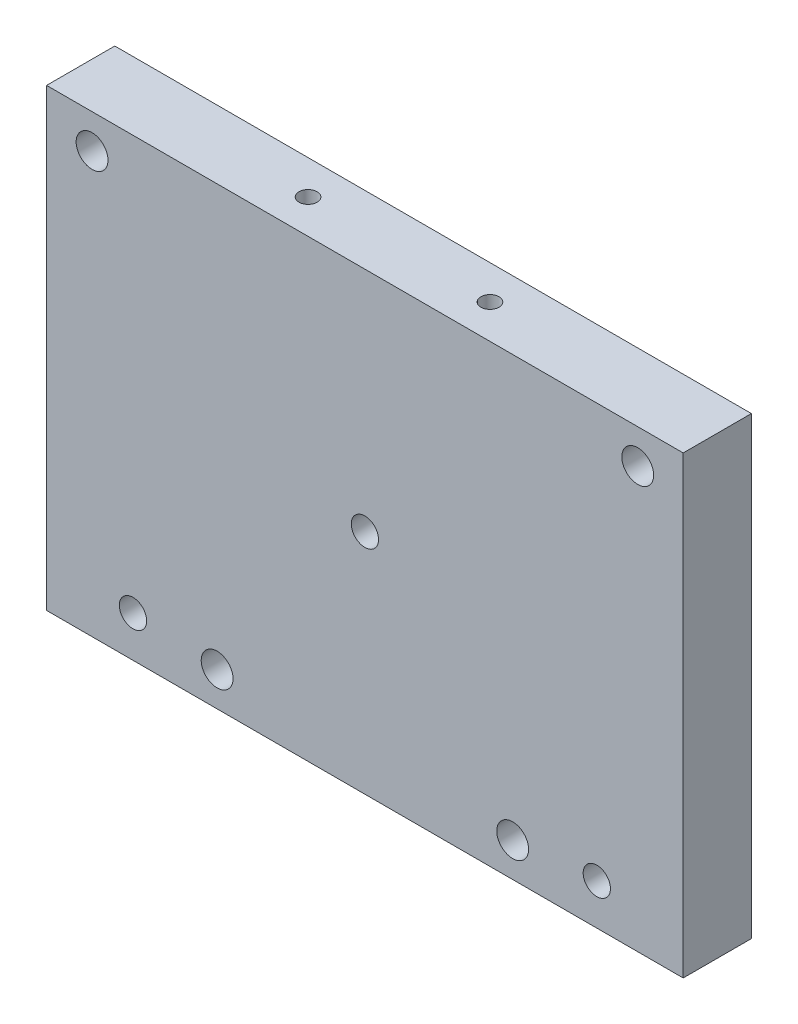
SolidWorks part; units mm, degrees
ref_plane "Front Plane" through (0, 0, 0) normal (0, 0, 1) x (1, 0, 0)
ref_plane "Top Plane" through (0, 0, 0) normal (0, 1, 0) x (1, 0, 0)
ref_plane "Right Plane" through (0, 0, 0) normal (1, 0, 0) x (0, 0, -1)
sketch "Sketch1" plane through (0, 0, 0) normal (0, 0, 1) x (1, 0, 0)
  line L1 (-140, -100) -> (140, -100)
  line L2 (-140, -100) -> (-140, 100)
  line L3 (-140, 100) -> (140, 100)
  line L4 (140, -100) -> (140, 100)
  circle A1 centre (-120, -85) radius 5
  circle A2 centre (120, -85) radius 5
  circle A3 centre (-65, -85) radius 5
  circle A4 centre (65, -85) radius 5
  circle A5 centre (65, 85) radius 5
  circle A6 centre (-65, 85) radius 5
  circle A7 centre (-120, 85) radius 5
  circle A8 centre (120, 85) radius 5
  circle A9 centre (0, 0) radius 6
  point P0 (0, 0)
  dimension "D1" = 2
  dimension "D2" = 2
  dimension "D4" = 2
  dimension "D3" = 2
  dimension "D5" = 2
extrude "Boss-Extrude1" add sketch "Sketch1" along normal blind 30
sketch "Sketch2" plane through (0, 0, 0) normal (0, 0, -1) x (-1, 0, 0)
  circle A0 centre (-120, 85) radius 7
  circle A1 centre (120, 85) radius 7
  circle A2 centre (65, -85) radius 7
  circle A3 centre (-65, -85) radius 7
extrude "Cut-Extrude1" cut sketch "Sketch2" against normal blind 30
sketch "Sketch3" plane through (0, 0, 30) normal (0, 0, 1) x (1, 0, 0)
  circle A0 centre (-120, -85) radius 5
  circle A1 centre (120, -85) radius 5
  circle A4 centre (-65, 85) radius 5
  circle A6 centre (65, 85) radius 5
extrude "Boss-Extrude3" add sketch "Sketch3" against normal blind 10
sketch "Sketch4" plane through (0, 0, 30) normal (0, 0, 1) x (1, 0, 0)
  circle A0 centre (-102, -82) radius 6
  circle A1 centre (102, -82) radius 6
extrude "Cut-Extrude2" cut sketch "Sketch4" against normal blind 30
sketch "Sketch5" plane through (0, -100, 0) normal (0, -1, 0) x (-1, 0, 0)
  circle A0 centre (40, -15) radius 4
  circle A1 centre (-40, -15) radius 4
extrude "Cut-Extrude3" cut sketch "Sketch5" against normal blind 200
sketch "Sketch6" plane through (0, 0, 0) normal (0, 0, 1) x (1, 0, 0)
  line L170 (-11.1043, 17.9451) -> (-10.2238, 17.945)
  line L171 (1.8403, 22.2139) -> (2.7208, 22.2138)
  line L172 (2.7208, 22.2138) -> (2.7206, 16.178)
  line L173 (2.7206, 16.178) -> (1.8401, 16.178)
  line L174 (1.8401, 16.178) -> (1.8403, 22.2139)
  line L175 (-7.2931, 26.845) -> (-4.0902, 26.8449)
  line L176 (-4.0902, 25.9644) -> (-5.1746, 25.9644)
  line L177 (-4.0902, 26.8449) -> (-4.0902, 25.9644)
  line L178 (-1.5772, 16.1782) -> (-0.6967, 16.1781)
  line L179 (-0.6967, 16.1781) -> (-0.6964, 26.7271)
  line L180 (-1.5769, 26.7271) -> (-1.5772, 16.1782)
  line L181 (9.866, 20.9147) -> (9.866, 21.8129)
  line L182 (9.8658, 15.9429) -> (9.8658, 16.8411)
  line L183 (-1.5769, 26.7271) -> (-0.6964, 26.7271)
  line L184 (9.866, 21.8129) -> (10.7465, 21.8129)
  line L185 (10.7465, 21.8129) -> (10.5996, 15.9428)
  line L186 (10.5996, 15.9428) -> (9.8658, 15.9429)
  line L187 (1.8404, 25.8041) -> (1.8404, 26.727)
  line L188 (1.8403, 23.4157) -> (10.7465, 23.4154)
  line L189 (1.8403, 23.4157) -> (1.8404, 24.2952)
  line L190 (10.7465, 23.4154) -> (10.7466, 24.2949)
  line L191 (10.7466, 24.2949) -> (1.8404, 24.2952)
  line L192 (1.8404, 25.8041) -> (10.7466, 25.8038)
  line L193 (10.7466, 25.8038) -> (10.7466, 26.7267)
  line L194 (10.7466, 26.7267) -> (1.8404, 26.727)
  arc A43 (-5.6229, 21.3776) -> (-5.1746, 25.9644) centre (-7.2931, 23.8562) ccw
  circle A44 centre (-7.2931, 23.8562) radius 2.1083
  arc A45 (-10.2238, 17.945) -> (-7.0978, 20.8738) centre (-7.2888, 17.945) ccw
  arc A46 (-11.1043, 17.9451) -> (-5.6229, 21.3776) centre (-7.2888, 17.945) ccw
  arc A47 (-7.2931, 26.845) -> (-7.0978, 20.8738) centre (-7.2931, 23.8562) ccw
  arc A48 (9.866, 20.9147) -> (9.8658, 16.8411) centre (7.4059, 18.878) ccw
  circle A49 centre (7.4059, 18.878) radius 2.3132
  point P121 (10.5997, 18.8779)
extrude "Cut-Extrude7" cut sketch "Sketch6" along normal blind 0.6
